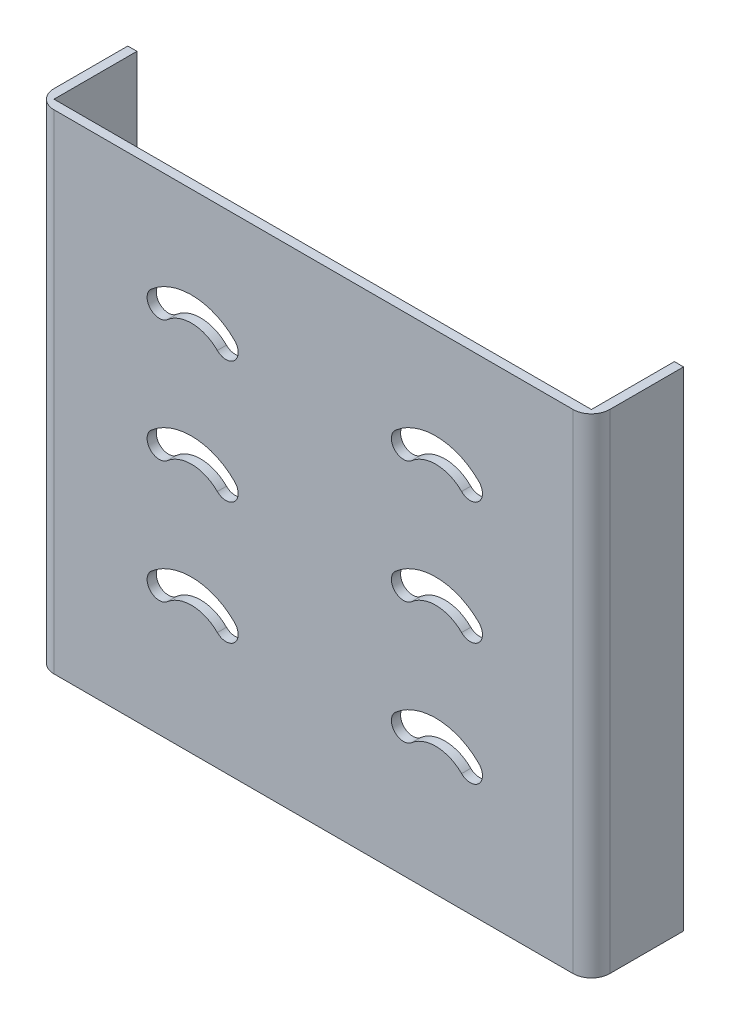
SolidWorks part; units mm, degrees
ref_plane "Front Plane" through (0, 0, 0) normal (0, 0, 1) x (1, 0, 0)
ref_plane "Top Plane" through (0, 0, 0) normal (0, 1, 0) x (1, 0, 0)
ref_plane "Right Plane" through (0, 0, 0) normal (1, 0, 0) x (0, 0, -1)
sketch "Sketch1" plane through (0, 0, 0) normal (0, 1, 0) x (1, 0, 0)
  line L0 (-45.5, 0) -> (45.5, 0)
  line L1 (45.5, 0) -> (45.5, 15.0837)
  line L2 (45.5, 15.0837) -> (44, 15.0837)
  line L3 (44, 15.0837) -> (44, 1.5)
  line L4 (44, 1.5) -> (-44, 1.5)
  line L5 (-44, 1.5) -> (-44, 15.0837)
  line L6 (-44, 15.0837) -> (-45.5, 15.0837)
  line L7 (-45.5, 15.0837) -> (-45.5, 0)
  point P3 (41.5, 0)
  point P4 (0, 0)
  dimension "D1" = 91
  dimension "D2" = 88
  dimension "D3" = 1.5
  dimension "D4" = 1.5
extrude "Boss-Extrude1" add sketch "Sketch1" along normal blind 80
fillet "Fillet1" radius 3 2 edges at (45.5, 40, 0) (-45.5, 40, 0)
sketch "Sketch2" plane through (0, 0, 0) normal (0, 0, 1) x (1, 0, 0)
  arc A0 (-25.2516, 61.035) -> (-14.3431, 60.6569) centre (-20, 55) cw construction
  arc A1 (-12.9289, 62.0711) -> (-26.5645, 62.5437) centre (-20, 55) ccw
  arc A2 (-15.7574, 59.2426) -> (-23.9387, 59.5262) centre (-20, 55) ccw
  arc A3 (-15.7574, 59.2426) -> (-12.9289, 62.0711) centre (-14.3431, 60.6569) ccw
  arc A4 (-26.5645, 62.5437) -> (-23.9387, 59.5262) centre (-25.2516, 61.035) ccw
  arc A5 (14.7484, 61.035) -> (25.6569, 60.6569) centre (20, 55) cw construction
  arc A6 (27.0711, 62.0711) -> (13.4355, 62.5437) centre (20, 55) ccw
  arc A7 (24.2426, 59.2426) -> (16.0613, 59.5262) centre (20, 55) ccw
  arc A8 (24.2426, 59.2426) -> (27.0711, 62.0711) centre (25.6569, 60.6569) ccw
  arc A9 (13.4355, 62.5437) -> (16.0613, 59.5262) centre (14.7484, 61.035) ccw
  arc A10 (14.7484, 41.035) -> (25.6569, 40.6569) centre (20, 35) cw construction
  arc A11 (27.0711, 42.0711) -> (13.4355, 42.5437) centre (20, 35) ccw
  arc A12 (24.2426, 39.2426) -> (16.0613, 39.5262) centre (20, 35) ccw
  arc A13 (24.2426, 39.2426) -> (27.0711, 42.0711) centre (25.6569, 40.6569) ccw
  arc A14 (13.4355, 42.5437) -> (16.0613, 39.5262) centre (14.7484, 41.035) ccw
  arc A15 (14.7484, 21.035) -> (25.6569, 20.6569) centre (20, 15) cw construction
  arc A16 (27.0711, 22.0711) -> (13.4355, 22.5437) centre (20, 15) ccw
  arc A17 (24.2426, 19.2426) -> (16.0613, 19.5262) centre (20, 15) ccw
  arc A18 (24.2426, 19.2426) -> (27.0711, 22.0711) centre (25.6569, 20.6569) ccw
  arc A19 (13.4355, 22.5437) -> (16.0613, 19.5262) centre (14.7484, 21.035) ccw
  arc A20 (-25.2516, 41.035) -> (-14.3431, 40.6569) centre (-20, 35) cw construction
  arc A21 (-12.9289, 42.0711) -> (-26.5645, 42.5437) centre (-20, 35) ccw
  arc A22 (-15.7574, 39.2426) -> (-23.9387, 39.5262) centre (-20, 35) ccw
  arc A23 (-15.7574, 39.2426) -> (-12.9289, 42.0711) centre (-14.3431, 40.6569) ccw
  arc A24 (-26.5645, 42.5437) -> (-23.9387, 39.5262) centre (-25.2516, 41.035) ccw
  arc A25 (-25.2516, 21.035) -> (-14.3431, 20.6569) centre (-20, 15) cw construction
  arc A26 (-12.9289, 22.0711) -> (-26.5645, 22.5437) centre (-20, 15) ccw
  arc A27 (-15.7574, 19.2426) -> (-23.9387, 19.5262) centre (-20, 15) ccw
  arc A28 (-15.7574, 19.2426) -> (-12.9289, 22.0711) centre (-14.3431, 20.6569) ccw
  arc A29 (-26.5645, 22.5437) -> (-23.9387, 19.5262) centre (-25.2516, 21.035) ccw
  point P3 (-19.7229, 62.9952)
  point P15 (20.2771, 62.9952)
  point P23 (20.2771, 42.9952)
  point P31 (20.2771, 22.9952)
  point P39 (-19.7229, 42.9952)
  point P47 (-19.7229, 22.9952)
  dimension "D1" = 2
  dimension "D2" = 8
  dimension "D3" = 20
  dimension "D6" = 15
  dimension "D4" = 2
  dimension "D5" = 3
extrude "Cut-Extrude1" cut sketch "Sketch2" against normal up to surface (1.5 mm away) up to face at (0, 40, -1.5)
